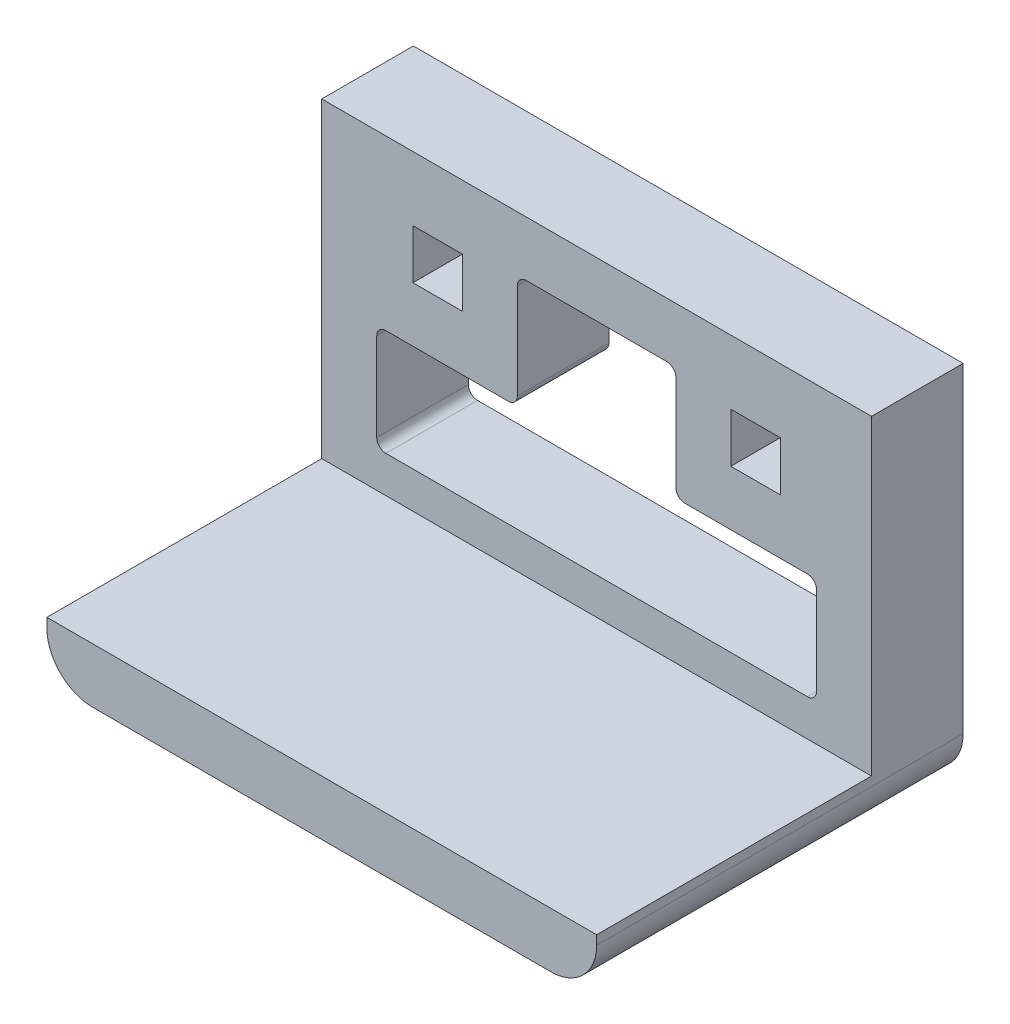
SolidWorks part; units mm, degrees
ref_plane "Front Plane" through (0, 0, 0) normal (1, 0, 0) x (0, 1, 0)
ref_plane "Top Plane" through (0, 0, 0) normal (0, 0, 1) x (0, 1, 0)
ref_plane "Right Plane" through (0, 0, 0) normal (0, 1, 0) x (-1, 0, 0)
sketch "Sketch1" plane through (0, 0, 0) normal (0, 0, 1) x (0, 1, 0)
  line L1 (-20, -30) -> (20, -30)
  line L2 (-20, -30) -> (-20, 30)
  line L3 (-20, 30) -> (20, 30)
  line L4 (20, -30) -> (20, 30)
  line L5 (-20, -30) -> (20, 30) construction
  line L6 (-20, 30) -> (20, -30) construction
  point P0 (0, 0)
extrude "Boss-Extrude1" add sketch "Sketch1" along normal blind 10
sketch "Sketch2" plane through (0, 0, 10) normal (0, 0, 1) x (1, 0, 0)
  line L0 (-30, 20) -> (-30, -20) construction
  line L1 (-20.05, 7.6) -> (-14.65, 7.6)
  line L2 (-20.05, 7.6) -> (-20.05, 13)
  line L3 (-20.05, 13) -> (-14.65, 13)
  line L4 (-14.65, 7.6) -> (-14.65, 13)
  line L5 (-20.05, 7.6) -> (-14.65, 13) construction
  line L6 (-20.05, 13) -> (-14.65, 7.6) construction
  line L7 (30, 20) -> (-30, 20) construction
  line L8 (0, 20.2271) -> (0, -20) construction
  line L9 (-30, -20) -> (30, -20) construction
  line L10 (20.05, 13) -> (14.65, 7.6) construction
  line L11 (20.05, 7.6) -> (14.65, 13) construction
  line L12 (14.65, 7.6) -> (14.65, 13)
  line L13 (20.05, 13) -> (14.65, 13)
  line L14 (20.05, 7.6) -> (20.05, 13)
  line L15 (20.05, 7.6) -> (14.65, 7.6)
  point P0 (-17.35, 10.3)
  point P17 (17.35, 10.3)
  dimension "D1" = 9.95
  dimension "D2" = 7
  dimension "D3" = 5.4
extrude "Cut-Extrude1" cut sketch "Sketch2" against normal through all
sketch "Sketch3" plane through (0, 0, 10) normal (0, 0, 1) x (1, 0, 0)
  line L0 (30, -20) -> (30, 20) construction
  line L1 (-30, -20) -> (30, -20)
  line L2 (-30, -20) -> (-30, -14)
  line L3 (-30, -14) -> (30, -14)
  line L4 (30, -20) -> (30, -14)
extrude "Boss-Extrude2" add sketch "Sketch3" along normal blind 30
sketch "Sketch4" plane through (0, 0, 10) normal (0, 0, 1) x (1, 0, 0)
  line L1 (-24, 1.6) -> (-8.65, 1.6)
  line L2 (-24, 1.6) -> (-24, -10)
  line L3 (-24, -10) -> (24, -10)
  line L4 (24, 1.6) -> (24, -10)
  line L5 (-30, 20) -> (-30, -14) construction
  line L6 (30, -14) -> (30, 20) construction
  line L7 (14.65, 7.6) -> (20.05, 7.6) construction
  line L9 (-8.65, 14) -> (8.65, 14)
  line L10 (-8.65, 14) -> (-8.65, 1.6)
  line L12 (8.65, 14) -> (8.65, 1.6)
  line L13 (-14.65, 7.6) -> (-14.65, 13) construction
  line L14 (14.65, 13) -> (14.65, 7.6) construction
  line L16 (30, 20) -> (-30, 20) construction
  line L17 (8.65, 1.6) -> (24, 1.6)
  line L18 (30, -14) -> (-30, -14) construction
  dimension "D1" = 6
  dimension "D2" = 6
  dimension "D3" = 6
  dimension "D4" = 6
  dimension "D5" = 6
  dimension "D6" = 6
  dimension "D7" = 4
extrude "Cut-Extrude2" cut sketch "Sketch4" against normal through all
fillet "Fillet2" radius 1 8 edges at (24, -10, 5) (-24, -10, 5) (-24, 1.6, 5) (24, 1.6, 5) (8.65, 14, 5) (-8.65, 14, 5) (-8.65, 1.6, 5) (8.65, 1.6, 5)
fillet "Fillet3" radius 5 2 edges at (-30, -20, 20) (30, -20, 20)
